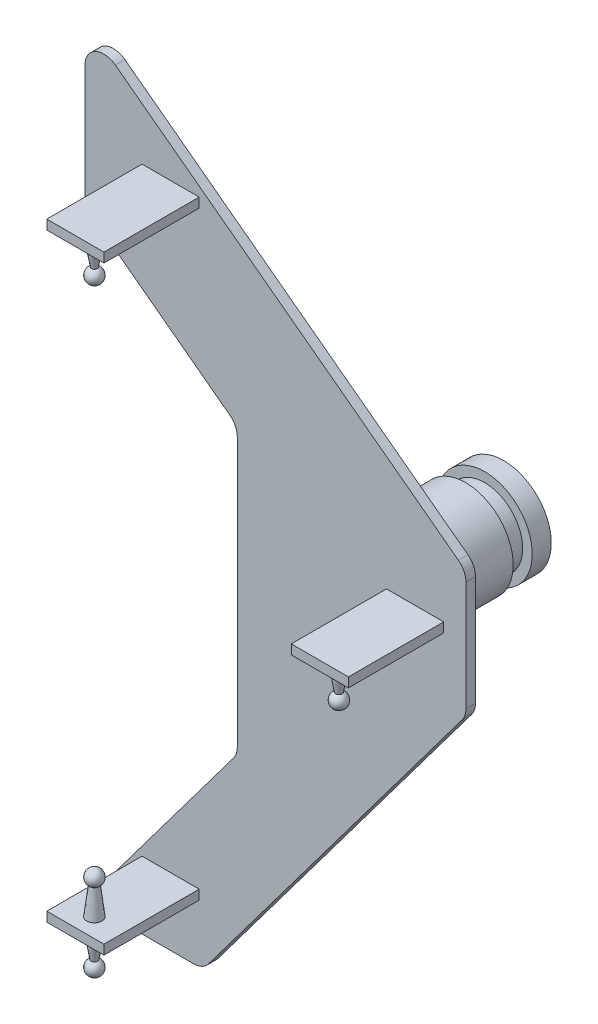
SolidWorks part; units mm, degrees
material "2014-T4"
ref_plane "Piano frontale" through (0, 0, 0) normal (0, 0, 1) x (1, 0, 0)
ref_plane "Piano superiore" through (0, 0, 0) normal (0, 1, 0) x (1, 0, 0)
ref_plane "Piano destro" through (0, 0, 0) normal (1, 0, 0) x (0, 0, -1)
sketch "Schizzo2" plane through (0, 0, 0) normal (0, 0, 1) x (1, 0, 0)
  line L1 (0, 0) -> (200, 0)
  line L2 (0, 0) -> (0, 400)
  line L3 (0, 400) -> (200, 400)
  line L4 (200, 0) -> (200, 400)
  dimension "D1" = 400
  dimension "D2" = 200
extrude "Estrusione-Estrusione2" add sketch "Schizzo2" along normal blind 5
sketch "Schizzo3" plane through (0, 0, 5) normal (0, 0, 1) x (1, 0, 0)
  line L0 (200, 400) -> (0, 400) construction
  line L2 (0, 400) -> (0, 0) construction
  line L3 (60, 350) -> (30, 350)
  line L4 (60, 350) -> (60, 345)
  line L5 (60, 345) -> (30, 345)
  line L6 (30, 350) -> (30, 345)
  line L7 (60, 30.4) -> (30, 30.4)
  line L8 (60, 30.4) -> (60, 35.4)
  line L9 (60, 35.4) -> (30, 35.4)
  line L10 (30, 30.4) -> (30, 35.4)
  line L11 (188.3376, 216.0608) -> (158.3376, 216.0608)
  line L12 (188.3376, 216.0608) -> (188.3376, 221.0608)
  line L13 (188.3376, 221.0608) -> (158.3376, 221.0608)
  line L14 (158.3376, 216.0608) -> (158.3376, 221.0608)
  point P0 (60, 350)
  point P5 (60, 30.4)
  point P14 (188.3376, 216.0608)
  dimension "D1" = 50
  dimension "D2" = 30
  dimension "D3" = 30
  dimension "D4" = 319.6
  dimension "D5" = 30
  dimension "D6" = 5
  dimension "D7" = 30
  dimension "D8" = 5
  dimension "D9" = 185.5
  dimension "D10" = 225.7
  dimension "D11" = 30
  dimension "D12" = 5
extrude "Estrusione-Estrusione3" add sketch "Schizzo3" along normal blind 50
sketch "Schizzo4" plane through (0, 345, 0) normal (0, -1, 0) x (-1, 0, 0)
  line L1 (-30, -55) -> (-60, -55) construction
  line L2 (-60, -55) -> (-60, -5) construction
  circle A0 centre (-45, -45) radius 4
  point P0 (-45, -45)
  dimension "D1" = 10
  dimension "D2" = 15
extrude "Estrusione-Estrusione4" add sketch "Schizzo4" along normal blind 15 draft 10 separate body
sketch "Schizzo9" plane through (0, 330, 0) normal (0, -1, 0) x (-1, 0, 0)
  point P0 (-45, -45)
ref_plane "Piano2" through (0, 0, 45) normal (0, 0, 1) x (1, 0, 0)
sketch "Schizzo10" plane through (0, 0, 45) normal (0, 0, 1) x (1, 0, 0)
  line L0 (41, 327) -> (49, 327)
  arc A0 (49, 327) -> (41, 327) centre (45, 327) ccw
  dimension "D2" = 8
  dimension "D3" = 0
  dimension "D1" = 3
revolve "Rivoluzione1" add sketch "Schizzo10" angle 360 about L0
sketch "Schizzo12" plane through (0, 216.0608, 0) normal (0, -1, 0) x (-1, 0, 0)
  line L0 (-158.3376, -55) -> (-158.3376, -5) construction
  line L1 (-158.3376, -55) -> (-188.3376, -55) construction
  circle A0 centre (-173.3376, -45) radius 4
  point P0 (-173.3376, -45)
  dimension "D1" = 15
  dimension "D2" = 10
extrude "Estrusione-Estrusione5" add sketch "Schizzo12" along normal blind 15 draft 9
sketch "Schizzo13" plane through (0, 201.0608, 0) normal (0, -1, 0) x (-1, 0, 0)
  point P0 (-173.3376, -45)
ref_plane "Piano3" through (0, 0, 45) normal (0, 0, 1) x (1, 0, 0)
sketch "Schizzo14" plane through (0, 0, 45) normal (0, 0, 1) x (1, 0, 0)
  line L0 (169.349, 198.0608) -> (177.349, 198.0608)
  arc A0 (177.349, 198.0608) -> (169.349, 198.0608) centre (173.349, 198.0608) ccw
  dimension "D2" = 3
  dimension "D1" = 8
revolve "Rivoluzione2" add sketch "Schizzo14" angle 360 about L0
sketch "Schizzo15" plane through (0, 30.4, 0) normal (0, -1, 0) x (-1, 0, 0)
  line L0 (-30, -55) -> (-60, -55) construction
  line L1 (-60, -55) -> (-60, -5) construction
  circle A0 centre (-45, -45) radius 4
  point P0 (-45, -45)
  dimension "D1" = 10
  dimension "D2" = 15
extrude "Estrusione-Estrusione6" add sketch "Schizzo15" along normal blind 15 draft 9
sketch "Schizzo17" plane through (0, 15.4, 0) normal (0, -1, 0) x (-1, 0, 0)
  point P0 (-45, -45)
sketch "Schizzo18" plane through (0, 0, 45) normal (0, 0, 1) x (1, 0, 0)
  line L0 (41, 12.4) -> (49, 12.4)
  arc A0 (49, 12.4) -> (41, 12.4) centre (45, 12.4) ccw
  dimension "D2" = 0
  dimension "D1" = 8
  dimension "D3" = 3
revolve "Rivoluzione3" add sketch "Schizzo18" angle 360 about L0
sketch "Schizzo21" plane through (0, 0, 0) normal (0, 0, -1) x (-1, 0, 0)
  line L0 (0, 400) -> (-200, 400)
  line L1 (-200, 400) -> (-200, 250)
  line L2 (-200, 0) -> (-200, 400) construction
  line L3 (-200, 250) -> (0, 400)
  line L4 (-200, 0) -> (-200, 184)
  line L5 (-200, 184) -> (-62, 0)
  line L6 (-62, 0) -> (-200, 0)
  line L7 (0, 180.2346) -> (0, 316.0032)
  line L8 (0, 316.0032) -> (-80, 256.0032)
  line L9 (-80, 256.0032) -> (-80, 106.6667)
  line L10 (-80, 106.6667) -> (0, 0)
  line L11 (0, 0) -> (0, 180.2346)
  dimension "D1" = 100
  dimension "D2" = 250
  dimension "D3" = 230
extrude "Taglio-Estrusione1" cut sketch "Schizzo21" against normal through all
fillet "Raccordo1" radius 10 8 edges at (62, 0, 2.5) (0, 0, 2.5) (0, 400, 2.5) (0, 316.0032, 2.5) (200, 184, 2.5) (200, 250, 2.5) (80, 106.6667, 2.5) (80, 256.0032, 2.5)
sketch "Schizzo22" plane through (0, 0, 0) normal (0, 0, -1) x (-1, 0, 0)
  circle A0 centre (-109.819, 175.1506) radius 25
  dimension "D1" = 172.4
  dimension "D2" = 68.6
extrude "Estrusione-Estrusione7" add sketch "Schizzo22" along normal blind 85
sketch "Schizzo23" plane through (0, 0, -85) normal (0, 0, -1) x (-1, 0, 0)
  circle A0 centre (-109.819, 175.1506) radius 20
extrude "Estrusione-Estrusione8" add sketch "Schizzo23" along normal blind 10
sketch "Schizzo24" plane through (0, 0, -95) normal (0, 0, -1) x (-1, 0, 0)
  circle A0 centre (-109.819, 175.1506) radius 25
extrude "Estrusione-Estrusione9" add sketch "Schizzo24" along normal blind 10
sketch "Schizzo25" plane through (0, 35.4, 0) normal (0, 1, 0) x (1, 0, 0)
  line L0 (60, -55) -> (60, -5) construction
  line L1 (60, -55) -> (30, -55) construction
  circle A0 centre (45, -45) radius 4
  dimension "D1" = 15
  dimension "D2" = 10
extrude "Estrusione-Estrusione10" add sketch "Schizzo25" along normal blind 15 draft 7
sketch "Schizzo27" plane through (0, 0, 45) normal (0, 0, 1) x (1, 0, 0)
  line L0 (47.1582, 50.4) -> (42.8418, 50.4) construction
  line L2 (41, 53.4) -> (49, 53.4)
  arc A0 (41, 53.4) -> (49, 53.4) centre (45, 53.4) ccw
  dimension "D1" = 3
  dimension "D2" = 8
revolve "Rivoluzione4" add sketch "Schizzo27" angle 360 about L2
ref_plane "Piano5" through (0, 0, 55) normal (0, 0, 1) x (1, 0, 0)
